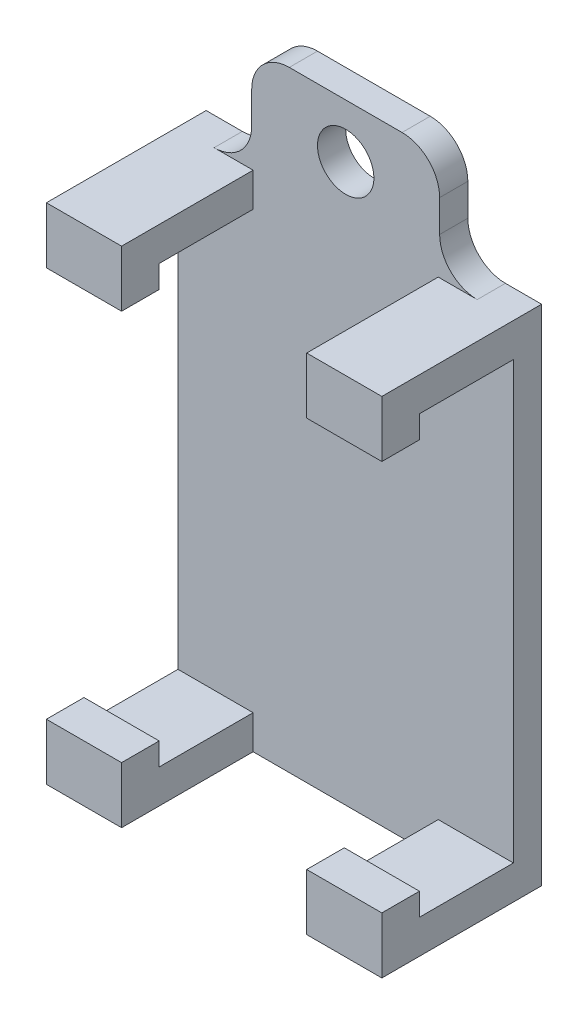
SolidWorks part; units mm, degrees
ref_plane "Front" through (0, 0, 0) normal (0, 0, 1) x (1, 0, 0)
ref_plane "Top" through (0, 0, 0) normal (0, 1, 0) x (1, 0, 0)
ref_plane "Right" through (0, 0, 0) normal (1, 0, 0) x (0, 0, -1)
sketch "Sketch1" plane through (0, 0, 0) normal (0, 1, 0) x (1, 0, 0)
  line L1 (0, 0) -> (17.85, 0)
  line L2 (0, 0) -> (0, 38.2)
  line L3 (0, 38.2) -> (17.85, 38.2)
  line L4 (17.85, 0) -> (17.85, 38.2)
  dimension "D1" = 17.85
  dimension "D2" = 38.2
extrude "Boss-Extrude1" add sketch "Sketch1" along normal blind 1.5
sketch "Sketch2" plane through (0, 1.5, 0) normal (0, 1, 0) x (1, 0, 0)
  line L0 (0, 38.2) -> (0, 0) construction
  line L1 (0, 29.5) -> (17.85, 29.5)
  line L2 (0, 29.5) -> (0, 32.5)
  line L3 (0, 32.5) -> (17.85, 32.5)
  line L4 (17.85, 29.5) -> (17.85, 32.5)
  line L5 (17.85, 0) -> (17.85, 38.2) construction
  line L7 (0, 8.7) -> (17.85, 8.7)
  line L8 (0, 8.7) -> (0, 5.7)
  line L9 (0, 5.7) -> (17.85, 5.7)
  line L10 (17.85, 8.7) -> (17.85, 5.7)
  line L11 (8.925, 8.7) -> (8.925, 29.5) construction
  point P14 (0, 19.1)
  point P15 (8.925, 19.1)
  dimension "D2" = 3
  dimension "D3" = 3
  dimension "D1" = 20.8
extrude "Boss-Extrude2" add sketch "Sketch2" along normal blind 7
sketch "Sketch3" plane through (0, 0, -29.5) normal (0, 0, 1) x (1, 0, 0)
  line L0 (17.85, 8.5) -> (17.85, 1.5) construction
  line L1 (0, 1.5) -> (17.85, 1.5)
  line L2 (0, 1.5) -> (0, 6.5)
  line L3 (0, 6.5) -> (17.85, 6.5)
  line L4 (17.85, 1.5) -> (17.85, 6.5)
  dimension "D1" = 5
extrude "Cut-Extrude1" cut sketch "Sketch3" against normal blind 1.2
sketch "Sketch4" plane through (0, 0, -8.7) normal (0, 0, -1) x (-1, 0, 0)
  line L0 (0, 8.5) -> (0, 1.5) construction
  line L1 (-17.85, 1.5) -> (0, 1.5)
  line L2 (-17.85, 1.5) -> (-17.85, 6.5)
  line L3 (-17.85, 6.5) -> (0, 6.5)
  line L4 (0, 1.5) -> (0, 6.5)
  dimension "D1" = 5
extrude "Cut-Extrude2" cut sketch "Sketch4" against normal blind 1.2
sketch "Sketch5" plane through (0, 1.5, 0) normal (0, 1, 0) x (1, 0, 0)
  line L0 (0, 38.2) -> (0, 32.5) construction
  line L1 (17.85, 38.2) -> (0, 38.2) construction
  line L2 (0, 5.7) -> (0, 0) construction
  circle A0 centre (8.925, 35.35) radius 1.5
  circle A1 centre (8.925, 2.85) radius 1.5
  point P6 (0, 35.35)
  point P9 (8.925, 38.2)
  point P12 (0, 2.85)
  dimension "D1" = 3
  dimension "D2" = 3
extrude "Cut-Extrude3" cut sketch "Sketch5" against normal through all
sketch "Sketch6" plane through (0, 0, 0) normal (0, -1, 0) x (1, 0, 0)
  line L0 (8.925, -35.35) -> (8.925, -5.7)
  line L1 (0, -5.7) -> (17.85, -5.7) construction
sketch "Sketch7" plane through (0, 0, 0) normal (0, 1, 0) x (1, 0, 0)
  line L1 (0, 5.7) -> (17.85, 5.7)
  line L2 (0, 5.7) -> (0, 0)
  line L3 (0, 0) -> (17.85, 0)
  line L4 (17.85, 5.7) -> (17.85, 0)
extrude "Cut-Extrude4" cut sketch "Sketch7" along normal through all
sketch "Sketch8" plane through (0, 0, -5.7) normal (0, 0, 1) x (1, 0, 0)
  line L0 (0, 8.5) -> (17.85, 8.5) construction
  line L1 (4, 8.5) -> (13.85, 8.5)
  line L2 (4, 8.5) -> (4, 1.5)
  line L3 (4, 1.5) -> (13.85, 1.5)
  line L4 (13.85, 8.5) -> (13.85, 1.5)
  line L5 (0, 1.5) -> (17.85, 1.5) construction
  line L6 (0, 1.5) -> (4, 1.5) construction
  line L16 (0, 8.5) -> (0, 0) construction
  point P8 (8.925, 8.5)
  point P9 (8.925, 8.5)
  dimension "D1" = 4
extrude "Cut-Extrude5" cut sketch "Sketch8" against normal through all
sketch "Sketch9" plane through (0, 1.5, 0) normal (0, 1, 0) x (1, 0, 0)
  line L0 (4, 32.5) -> (0, 32.5) construction
  line L1 (0, 38.2) -> (3.925, 38.2)
  line L2 (0, 38.2) -> (0, 32.5)
  line L3 (0, 32.5) -> (3.925, 32.5)
  line L4 (3.925, 38.2) -> (3.925, 32.5)
  line L5 (8.925, 38.2) -> (8.925, 5.7) construction
  line L6 (17.85, 38.2) -> (0, 38.2) construction
  line L7 (4, 5.7) -> (13.85, 5.7) construction
  line L8 (13.925, 38.2) -> (13.925, 32.5)
  line L9 (17.85, 32.5) -> (13.925, 32.5)
  line L10 (17.85, 38.2) -> (17.85, 32.5)
  line L11 (17.85, 38.2) -> (13.925, 38.2)
  dimension "D1" = 5
extrude "Cut-Extrude6" cut sketch "Sketch9" against normal through all
fillet "Fillet1" radius 2 4 edges at (3.925, 0.75, -32.5) (3.925, 0.75, -38.2) (13.925, 0.75, -38.2) (13.925, 0.75, -32.5)
move or copy body "Body-Move/Copy1" bodies to move or copy 109 copy no rotation origin (0, 2.75, -20.7) rotation axis (1, 0, 0) rotation angle 90
equation "\"Board Length\" = 23.2'The dimension of the board parallel with the clips"
equation "\"Board Width\"= 17.85'The dimension of the board perpendicular to the clips"
equation "\"D1@Sketch1\"=\"Board Width\""
equation "\"Board Slot Length\"= \"Board Length\" - 2 * \"Overhang Cut\""
equation "\"Overhang Cut\"= 1.2"
equation "\"D1@Cut-Extrude1\"=\"Overhang Cut\""
equation "\"D1@Sketch2\"=\"Board Slot Length\""
equation "\"Mount Length\"= \"Board Length\" + 7.5 * 2"
equation "\"D2@Sketch1\"=\"Mount Length\""
